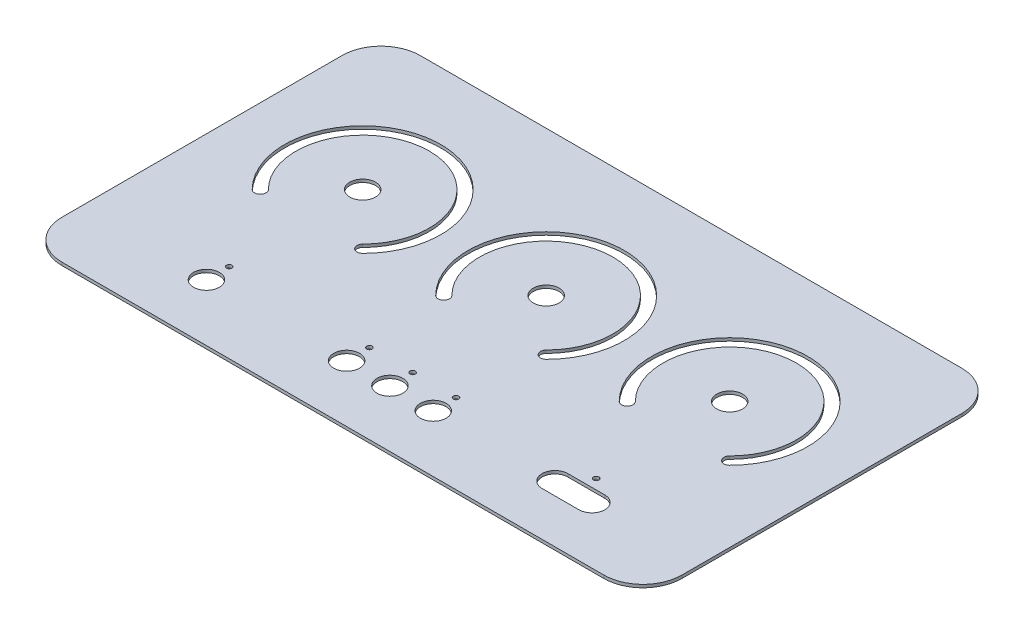
SolidWorks part; units mm, degrees
ref_plane "Front Plane" through (0, 0, 0) normal (0, 0, 1) x (1, 0, 0)
ref_plane "Top Plane" through (0, 0, 0) normal (0, 1, 0) x (1, 0, 0)
ref_plane "Right Plane" through (0, 0, 0) normal (1, 0, 0) x (0, 0, -1)
sketch "Sketch1" plane through (0, 0, 0) normal (0, 1, 0) x (1, 0, 0)
  line L0 (0, 59.325) -> (0, -59.325) construction
  line L1 (-102.69, -59.325) -> (102.69, -59.325)
  line L2 (-102.69, -59.325) -> (-102.69, 59.325)
  line L3 (-102.69, 59.325) -> (102.69, 59.325)
  line L4 (102.69, -59.325) -> (102.69, 59.325)
  line L5 (-102.69, -59.325) -> (102.69, 59.325) construction
  line L6 (-102.69, 59.325) -> (102.69, -59.325) construction
  line L7 (54.69, -40.445) -> (66.91, -40.445) construction
  line L8 (54.69, -36.17) -> (66.91, -36.17)
  line L9 (54.69, -44.72) -> (66.91, -44.72)
  line L10 (0, 11.325) -> (-18.307, -6.982) construction
  line L11 (-16.967, -5.642) -> (-15.6271, -6.982) construction
  line L12 (-60.8, 11.325) -> (0, 11.325) construction
  circle A0 centre (0, -40.445) radius 4.275
  circle A1 centre (-14.35, -40.445) radius 4.275
  circle A2 centre (0, -32.895) radius 0.89
  circle A3 centre (-14.35, -32.895) radius 0.89
  circle A4 centre (0, 11.325) radius 4.275
  circle A5 centre (-60.8, 11.325) radius 4.275
  circle A6 centre (-60.8, -32.895) radius 0.89
  circle A7 centre (14.35, -32.895) radius 0.89
  circle A8 centre (14.35, -40.445) radius 4.275
  circle A9 centre (60.8, -32.895) radius 0.89
  circle A10 centre (60.8, 11.325) radius 4.275
  circle A11 centre (-60.8, -40.445) radius 4.275
  arc A12 (54.69, -36.17) -> (54.69, -44.72) centre (54.69, -40.445) ccw
  arc A13 (66.91, -44.72) -> (66.91, -36.17) centre (66.91, -40.445) ccw
  arc A14 (18.307, -6.982) -> (-18.307, -6.982) centre (0, 11.325) ccw
  arc A15 (15.6271, -4.3021) -> (-15.6271, -4.3021) centre (0, 11.325) ccw
  arc A16 (-18.307, -6.982) -> (-15.6271, -4.3021) centre (-16.967, -5.642) ccw
  arc A17 (18.307, -6.982) -> (15.6271, -4.3021) centre (16.967, -5.642) cw
  arc A18 (-42.493, -6.982) -> (-45.1729, -4.3021) centre (-43.833, -5.642) cw
  arc A19 (-79.107, -6.982) -> (-76.4271, -4.3021) centre (-77.767, -5.642) ccw
  arc A20 (-79.107, -6.982) -> (-42.493, -6.982) centre (-60.8, 11.325) cw
  arc A21 (-76.4271, -4.3021) -> (-45.1729, -4.3021) centre (-60.8, 11.325) cw
  arc A22 (42.493, -6.982) -> (45.1729, -4.3021) centre (43.833, -5.642) ccw
  arc A23 (79.107, -6.982) -> (76.4271, -4.3021) centre (77.767, -5.642) cw
  arc A24 (79.107, -6.982) -> (42.493, -6.982) centre (60.8, 11.325) ccw
  arc A25 (76.4271, -4.3021) -> (45.1729, -4.3021) centre (60.8, 11.325) ccw
  point P0 (0, 11.325)
  point P33 (60.8, -40.445)
  point P42 (-15.6271, -4.3021)
  point P43 (-16.297, -6.312)
  point P51 (-30.4, 11.325)
  dimension "D3" = 8.55
  dimension "D4" = 8.55
  dimension "D6" = 1.78
  dimension "D7" = 1.78
  dimension "D9" = 8.55
  dimension "D10" = 8.55
  dimension "D12" = 1.78
  dimension "D13" = 8.55
  dimension "D15" = 4.275
  dimension "D17" = 14.35
  dimension "D1" = 205.38
  dimension "D2" = 118.65
  dimension "D5" = 18.88
  dimension "D8" = 7.55
  dimension "D11" = 60.8
  dimension "D14" = 6.11
  dimension "D16" = 70.65
extrude "Boss-Extrude1" add sketch "Sketch1" along normal blind 1
fillet "Fillet1" radius 12.94 4 edges at (-102.69, 0.5, 59.325) (102.69, 0.5, 59.325) (102.69, 0.5, -59.325) (-102.69, 0.5, -59.325)
